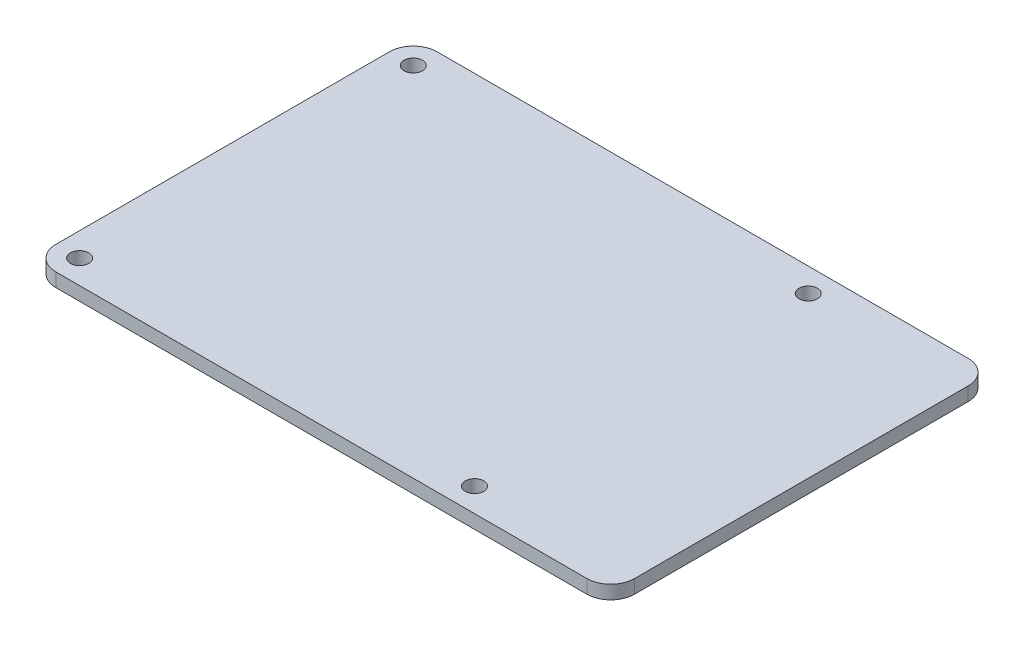
SolidWorks part; units mm, degrees
ref_plane "前视基准面" through (0, 0, 0) normal (0, 0, 1) x (1, 0, 0)
ref_plane "上视基准面" through (0, 0, 0) normal (0, 1, 0) x (1, 0, 0)
ref_plane "右视基准面" through (0, 0, 0) normal (1, 0, 0) x (0, 0, -1)
sketch "草图1" plane through (0, 0, 0) normal (0, 1, 0) x (1, 0, 0)
  line L1 (-42.5, 28) -> (42.5, 28)
  line L2 (-42.5, 28) -> (-42.5, -28)
  line L3 (-42.5, -28) -> (42.5, -28)
  line L4 (42.5, 28) -> (42.5, -28)
  line L5 (-42.5, 28) -> (42.5, -28) construction
  line L6 (-42.5, -28) -> (42.5, 28) construction
  point P0 (0, 0)
  dimension "D1" = 85
  dimension "D2" = 56
extrude "凸台-拉伸1" add sketch "草图1" along normal blind 2
sketch "草图2" plane through (0, 2, 0) normal (0, 1, 0) x (1, 0, 0)
  line L0 (-42.5, 28) -> (-42.5, -28) construction
  line L1 (42.5, 28) -> (-42.5, 28) construction
  circle A0 centre (-39, 24.5) radius 1.35
  circle A1 centre (19, 24.5) radius 1.35
  circle A2 centre (-39, -24.5) radius 1.35
  circle A3 centre (19, -24.5) radius 1.35
  point P8 (-37.9805, 24.4412)
  point P9 (-37.9805, -24.1774)
  point P10 (0, 0)
  point P11 (0, 0)
  point P12 (0, 0)
  dimension "D3" = 2.7
  dimension "D1" = 49
  dimension "D2" = 58
  dimension "D4" = 3.5
  dimension "D5" = 3.5
extrude "切除-拉伸1" cut sketch "草图2" against normal blind 2
fillet "圆角1" radius 3.5 4 edges at (42.5, 1, -28) (42.5, 1, 28) (-42.5, 1, -28) (-42.5, 1, 28)
